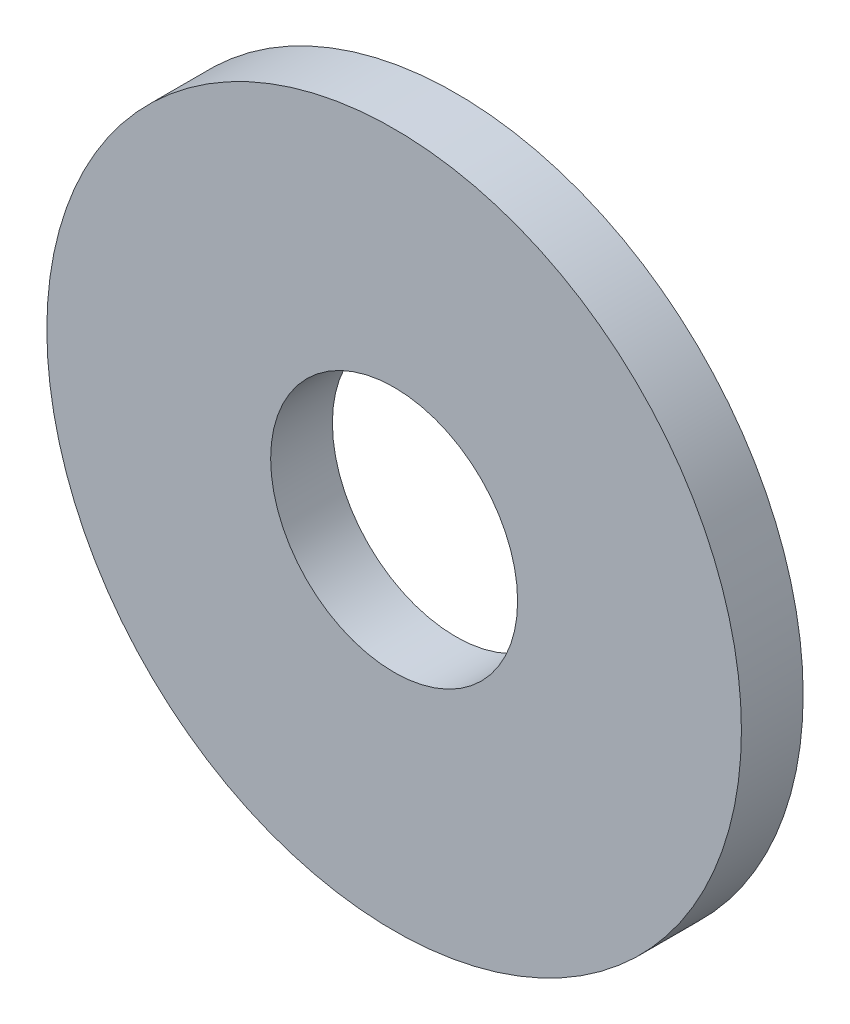
SolidWorks part; units mm, degrees
ref_plane "Front Plane" through (0, 0, 0) normal (0, 0, 1) x (1, 0, 0)
ref_plane "Top Plane" through (0, 0, 0) normal (0, 1, 0) x (1, 0, 0)
ref_plane "Right Plane" through (0, 0, 0) normal (1, 0, 0) x (0, 0, -1)
sketch "Ring Sketch" plane through (0, 0, 0) normal (0, 0, 1) x (1, 0, 0)
  circle A0 centre (0, 0) radius 4.5
  circle A1 centre (0, 0) radius 1.6
  dimension "D1" = 9
  dimension "D2" = 3.2
extrude "Ring Extrude" add sketch "Ring Sketch" along normal blind 0.8
equation "\"bore_diameter\"= 3.2mm 'Inner diameter; bearing or shaft interface"
equation "\"outside_diameter\"= 9mm 'Outer diameter of M3 large washer (DIN 9021)"
equation "\"width\"= 0.8mm 'Axial width of M3 large washer (DIN 9021)"
equation "\"D1@Ring Sketch\"= \"outside_diameter\""
equation "\"D2@Ring Sketch\"= \"bore_diameter\""
equation "\"D1@Ring Extrude\"= \"width\""
